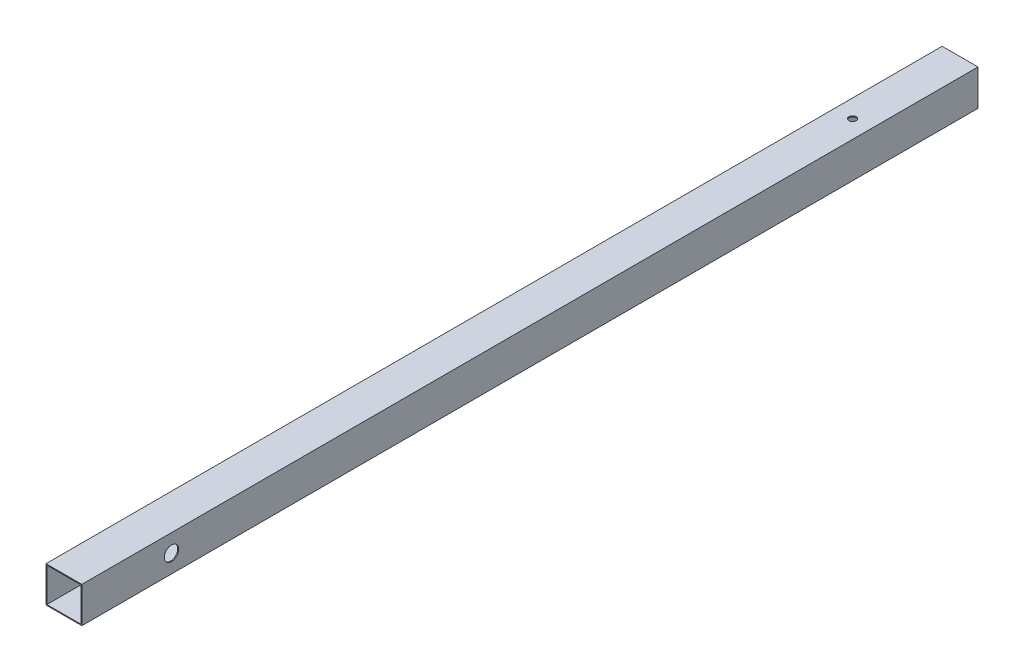
SolidWorks part; units mm, degrees
ref_plane "Front Plane" through (0, 0, 0) normal (0, 0, 1) x (1, 0, 0)
ref_plane "Top Plane" through (0, 0, 0) normal (0, 1, 0) x (1, 0, 0)
ref_plane "Right Plane" through (0, 0, 0) normal (1, 0, 0) x (0, 0, -1)
sketch "Sketch1" plane through (0, 0, 0) normal (0, 0, 1) x (1, 0, 0)
  line L1 (-10, 10) -> (10, 10)
  line L2 (-10, 10) -> (-10, -10)
  line L3 (-10, -10) -> (10, -10)
  line L4 (10, 10) -> (10, -10)
  line L5 (-10, 10) -> (10, -10) construction
  line L6 (-10, -10) -> (10, 10) construction
  point P0 (0, 0)
  dimension "D1" = 20
  dimension "D2" = 20
extrude "Boss-Extrude1" add sketch "Sketch1" along normal blind 500
sketch "Sketch2" plane through (0, 0, 0) normal (0, 0, -1) x (-1, 0, 0)
  line L1 (-9.5, 9.5) -> (9.5, 9.5)
  line L2 (-9.5, 9.5) -> (-9.5, -9.5)
  line L3 (-9.5, -9.5) -> (9.5, -9.5)
  line L4 (9.5, 9.5) -> (9.5, -9.5)
  line L5 (-9.5, 9.5) -> (9.5, -9.5) construction
  line L6 (-9.5, -9.5) -> (9.5, 9.5) construction
  point P0 (0, 0)
  dimension "D1" = 19
  dimension "D2" = 19
extrude "Cut-Extrude1" cut sketch "Sketch2" against normal through all
sketch "Sketch3" plane through (0, 10, 0) normal (0, 1, 0) x (1, 0, 0)
  line L0 (0, 0) -> (0, -60) construction
  circle A0 centre (0, -60) radius 2
  dimension "D2" = 4
  dimension "D1" = 60
extrude "Cut-Extrude2" cut sketch "Sketch3" against normal blind 20
sketch "Sketch5" plane through (-10, 0, 0) normal (-1, 0, 0) x (0, 0, 1)
  line L0 (0, 0) -> (450, 0) construction
  circle A0 centre (450, 0) radius 4
  dimension "D2" = 8
  dimension "D1" = 450
extrude "Cut-Extrude3" cut sketch "Sketch5" against normal blind 20
